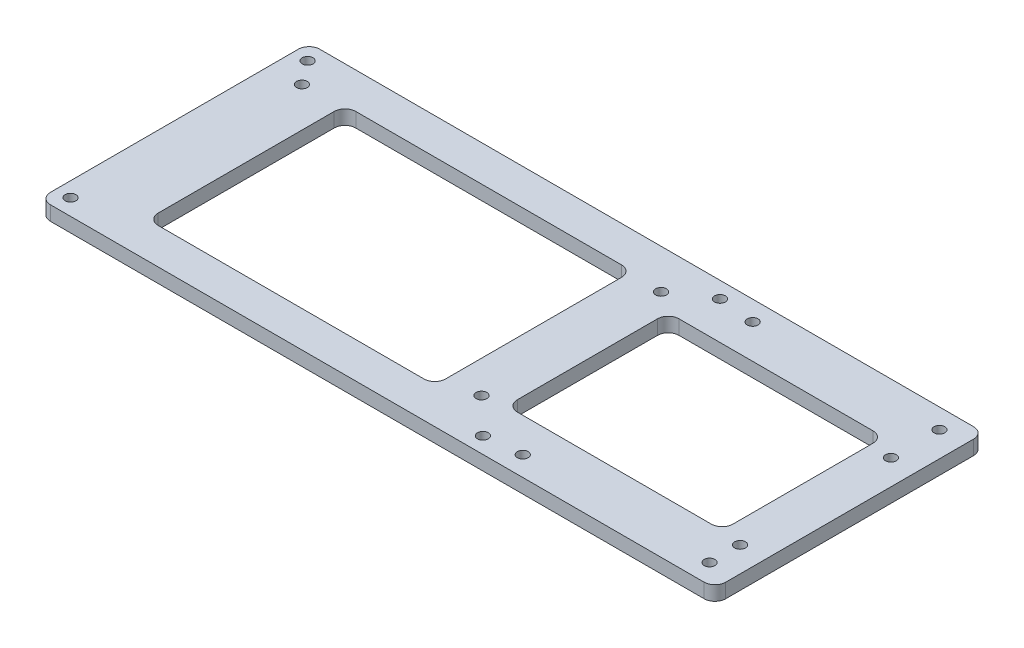
SolidWorks part; units mm, degrees
material "Thornel Mat VMA"
ref_plane "前视基准面" through (0, 0, 0) normal (0, 0, 1) x (1, 0, 0)
ref_plane "上视基准面" through (0, 0, 0) normal (0, 1, 0) x (1, 0, 0)
ref_plane "右视基准面" through (0, 0, 0) normal (1, 0, 0) x (0, 0, -1)
other "Configuration Table"
sketch "草图1" plane through (0, 0, 0) normal (0, 1, 0) x (1, 0, 0)
  line L0 (0, 0) -> (0, 102.0315) construction
  line L1 (-62.5, -37.5) -> (62.5, -37.5)
  line L2 (-62.5, -37.5) -> (-62.5, 37.5)
  line L3 (-62.5, 37.5) -> (62.5, 37.5)
  line L4 (62.5, -37.5) -> (62.5, 37.5)
  line L5 (-62.5, -37.5) -> (62.5, 37.5) construction
  line L6 (-62.5, 37.5) -> (62.5, -37.5) construction
  line L7 (0, 0) -> (92.167, 0) construction
  line L8 (0, 0) -> (83.8837, 0) construction
  line L9 (-1, 0) -> (-1, 59.4301) construction
  line L10 (37.5, 22.5) -> (37.5, -27.5)
  line L11 (-42.5, 27.5) -> (-42.5, 19.5)
  line L13 (37.5, -22.5) -> (37.5, 27.5)
  line L14 (37.5, 27.5) -> (-42.5, 27.5)
  line L15 (62.5, 37.5) -> (125.5, 37.5)
  line L16 (125.5, 37.5) -> (125.5, -37.5)
  line L17 (125.5, -37.5) -> (62.5, -37.5)
  line L18 (92.5, 0) -> (92.5, 58.5746) construction
  line L19 (52.5, -22.5) -> (112.5, -22.5)
  line L20 (52.5, -22.5) -> (52.5, 22.5)
  line L21 (52.5, 22.5) -> (112.5, 22.5)
  line L22 (112.5, -22.5) -> (112.5, 22.5)
  line L23 (52.5, -22.5) -> (112.5, 22.5) construction
  line L24 (52.5, 22.5) -> (112.5, -22.5) construction
  line L25 (37.5, -27.5) -> (-42.5, -27.5)
  line L26 (-42.5, -27.5) -> (-42.5, -19.5)
  line L27 (-42.5, 19.5) -> (-42.5, -19.5)
  circle A0 centre (-53.5, 26.5) radius 1.5
  circle A1 centre (46.5, 26.5) radius 1.5
  circle A2 centre (46.5, -23.5) radius 1.5
  circle A3 centre (-58.4, 33) radius 1.5
  circle A4 centre (56.4, 33) radius 1.5
  circle A5 centre (56.4, -33) radius 1.5
  circle A6 centre (-58.4, -33) radius 1.5
  circle A7 centre (118.5, 18.5) radius 1.5
  circle A8 centre (118.5, -23.5) radius 1.5
  circle A9 centre (118.5, 32) radius 1.5
  circle A10 centre (66.5, 32) radius 1.5
  circle A11 centre (118.5, -32) radius 1.5
  circle A12 centre (66.5, -32) radius 1.5
  point P0 (0, 0)
  point P39 (82.5, 0)
  dimension "D3" = 3
  dimension "D4" = 3
  dimension "D5" = 3
  dimension "D6" = 50
  dimension "D7" = 100
  dimension "D8" = 16
  dimension "D9" = 0
  dimension "D10" = 14
  dimension "D11" = 16
  dimension "D12" = 114.8
  dimension "D13" = 3
  dimension "D14" = 66
  dimension "D23" = 3
  dimension "D24" = 3
  dimension "D25" = 9.5
  dimension "D26" = 62.1
  dimension "D27" = 42
  dimension "D28" = 62.1
  dimension "D32" = 3
  dimension "D33" = 64
  dimension "D34" = 52
  dimension "D1" = 125
  dimension "D2" = 75
  dimension "D15" = 0
  dimension "D16" = 1
  dimension "D18" = 80
  dimension "D19" = 50
  dimension "D20" = 10
  dimension "D21" = 25
  dimension "D22" = 63
  dimension "D29" = 60
  dimension "D30" = 45
  dimension "D31" = 20
  dimension "D35" = 30
extrude "凸台-拉伸1" add sketch "草图1" along normal blind 4
fillet "圆角1" radius 3 12 edges at (-62.5, 2, -37.5) (37.5, 2, -27.5) (-42.5, 2, -27.5) (112.5, 2, -22.5) (112.5, 2, 22.5) (52.5, 2, 22.5) (52.5, 2, -22.5) (125.5, 2, -37.5) (125.5, 2, 37.5) (-62.5, 2, 37.5) (-42.5, 2, 27.5) (37.5, 2, 27.5)
